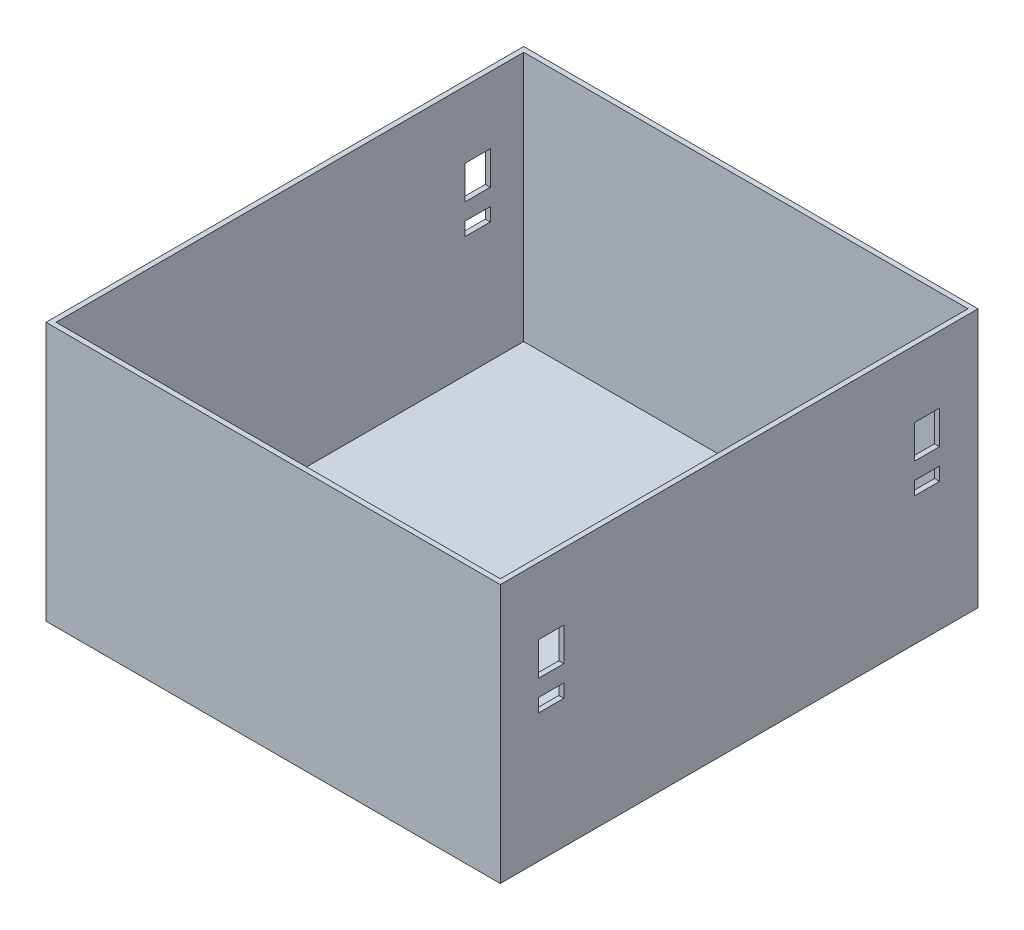
SolidWorks part; units mm, degrees
material "松木"
ref_plane "前基準面" through (0, 0, 0) normal (0, 0, 1) x (1, 0, 0)
ref_plane "上基準面" through (0, 0, 0) normal (0, 1, 0) x (1, 0, 0)
ref_plane "右基準面" through (0, 0, 0) normal (1, 0, 0) x (0, 0, -1)
sketch "草圖1" plane through (0, 0, 0) normal (0, 1, 0) x (1, 0, 0)
  line L1 (-136, 143) -> (136, 143)
  line L2 (-136, 143) -> (-136, -143)
  line L3 (-136, -143) -> (136, -143)
  line L4 (136, 143) -> (136, -143)
  line L5 (-136, 143) -> (136, -143) construction
  line L6 (-136, -143) -> (136, 143) construction
  line L7 (-133, 140) -> (133, 140)
  line L8 (-133, 140) -> (-133, -140)
  line L9 (-133, -140) -> (133, -140)
  line L10 (133, 140) -> (133, -140)
  line L11 (-133, 140) -> (133, -140) construction
  line L12 (-133, -140) -> (133, 140) construction
  point P0 (0, 0)
  point P5 (0, 0)
  dimension "D1" = 272
  dimension "D2" = 286
  dimension "D3" = 3
  dimension "D4" = 3
extrude "填料-伸長1" add sketch "草圖1" along normal blind 150
sketch "草圖2" plane through (0, 0, 0) normal (0, -1, 0) x (1, 0, 0)
  line L1 (-136, -143) -> (136, -143)
  line L2 (-136, -143) -> (-136, 143)
  line L3 (-136, 143) -> (136, 143)
  line L4 (136, -143) -> (136, 143)
extrude "填料-伸長2" add sketch "草圖2" along normal blind 5
sketch "草圖3" plane through (-136, 0, 0) normal (-1, 0, 0) x (0, 0, 1)
  line L0 (0, -5) -> (0, 150) construction
  line L1 (-120, 72) -> (-105, 72)
  line L2 (-120, 72) -> (-120, 80)
  line L3 (-120, 80) -> (-105, 80)
  line L4 (-105, 72) -> (-105, 80)
  line L5 (-120, 72) -> (-105, 80) construction
  line L6 (-120, 80) -> (-105, 72) construction
  line L7 (-120, 90) -> (-105, 90)
  line L8 (-120, 90) -> (-120, 110)
  line L9 (-120, 110) -> (-105, 110)
  line L10 (-105, 90) -> (-105, 110)
  line L11 (143, -5) -> (-143, -5) construction
  line L12 (-143, 150) -> (143, 150) construction
  point P0 (-112.5, 76)
  dimension "D1" = 10
  dimension "D2" = 8
  dimension "D3" = 20
  dimension "D4" = 15
  dimension "D5" = 120
  dimension "D6" = 60
extrude "除料-伸長1" cut sketch "草圖3" against normal through all
mirror "鏡射1" about plane through (0, 0, 0) normal (0, 0, 1) of "除料-伸長1"
